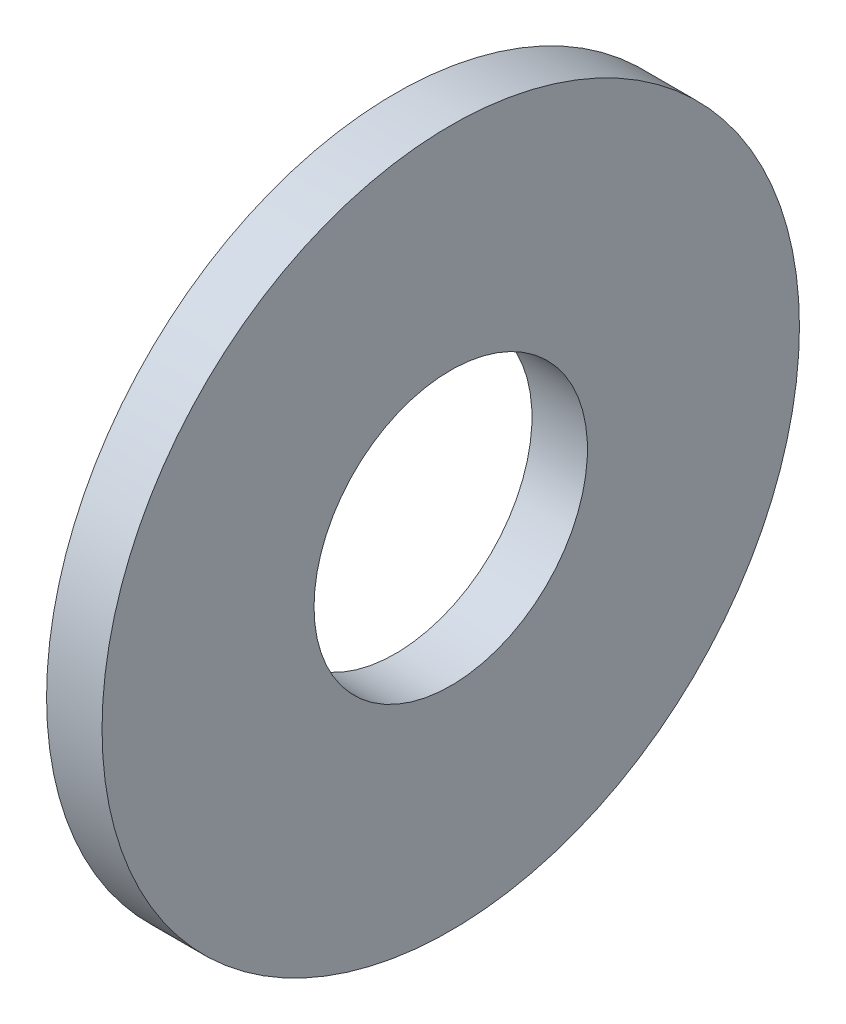
SolidWorks part; units mm, degrees
ref_plane "Plane1" through (0, 0, 0) normal (0, 0, 1) x (1, 0, 0)
ref_plane "Plane2" through (0, 0, 0) normal (0, 1, 0) x (1, 0, 0)
ref_plane "Plane3" through (0, 0, 0) normal (1, 0, 0) x (0, 0, -1)
other "Configuration Table"
sketch "Sketch1" plane through (0, 0, 0) normal (0, 0, 1) x (1, 0, 0)
  line L0 (-34.925, 0) -> (9.525, 0) construction
  line L1 (0, 8.625) -> (0, 22)
  line L2 (0, 22) -> (-3.5, 22)
  line L3 (-3.5, 22) -> (-3.5, 8.625)
  line L4 (-3.5, 8.625) -> (0, 8.625)
  dimension "Thickness" = 3.5
  dimension "Inside_dia" = 17.25
  dimension "Outside_dia" = 44
revolve "Base-Revolve" add sketch "Sketch1" angle 360 about L0
